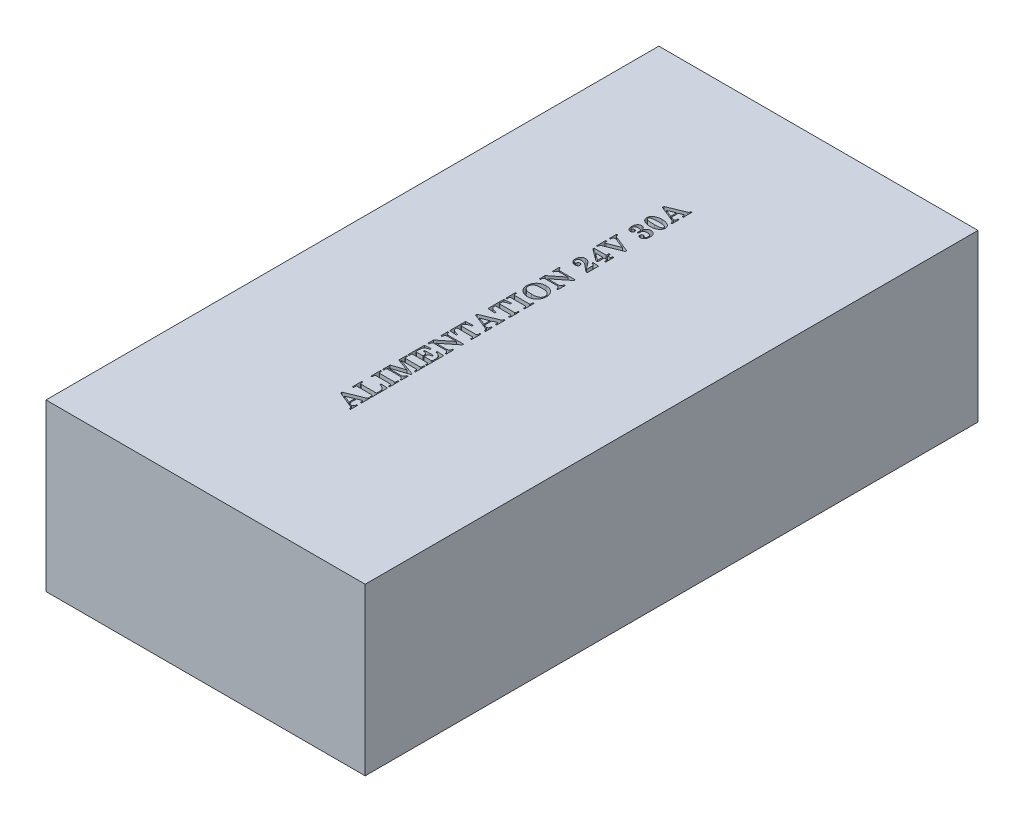
SolidWorks part; units mm, degrees
ref_plane "Plan de face" through (0, 0, 0) normal (0, 0, 1) x (1, 0, 0)
ref_plane "Plan de dessus" through (0, 0, 0) normal (0, 1, 0) x (1, 0, 0)
ref_plane "Plan de droite" through (0, 0, 0) normal (1, 0, 0) x (0, 0, -1)
sketch "Esquisse1" plane through (0, 0, 0) normal (0, 0, 1) x (1, 0, 0)
  line L1 (62.5, -32.5) -> (-62.5, -32.5)
  line L2 (62.5, -32.5) -> (62.5, 32.5)
  line L3 (62.5, 32.5) -> (-62.5, 32.5)
  line L4 (-62.5, -32.5) -> (-62.5, 32.5)
  line L5 (62.5, -32.5) -> (-62.5, 32.5) construction
  line L6 (62.5, 32.5) -> (-62.5, -32.5) construction
  point P0 (0, 0)
  dimension "D1" = 65
  dimension "D2" = 125
extrude "Boss.-Extru.1" add sketch "Esquisse1" against normal blind 240
sketch "Esquisse2" plane through (0, 32.5, 0) normal (0, 1, 0) x (1, 0, 0)
  line L0 (0.3498, 0) -> (0.3498, 240) construction
  line L1 (62.5, 0) -> (-62.5, 0) construction
  line L2 (62.5, 240) -> (-62.5, 240) construction
  text T0 "<b>ALIMENTATION 24V 30A</b>" font "Century Schoolbook" height in points 28
extrude "Enlèv. mat.-Extru.1" cut sketch "Esquisse2" against normal blind 10
